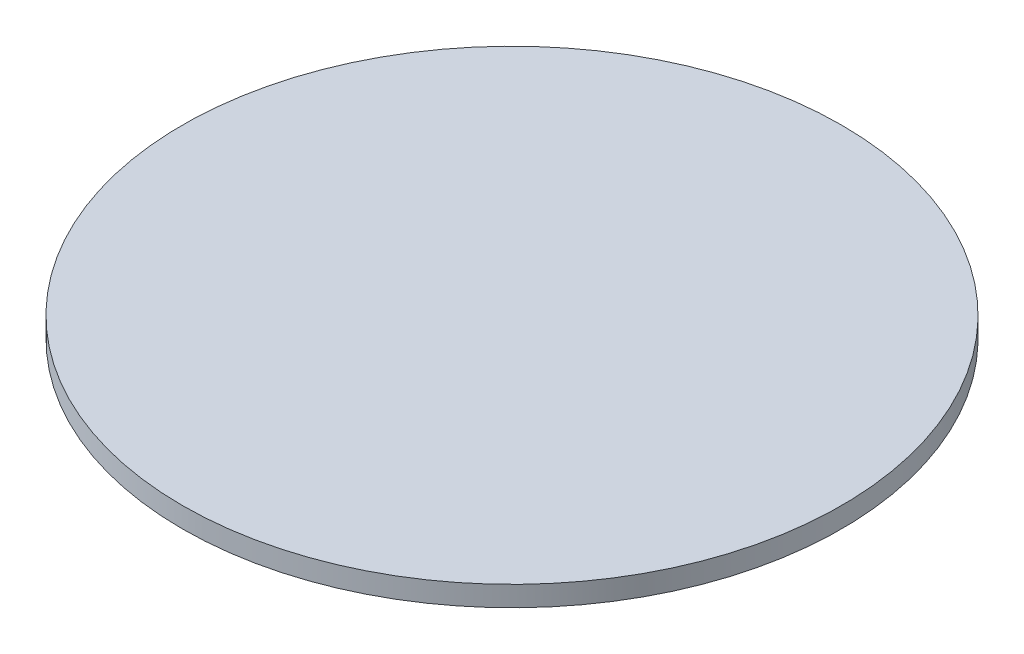
SolidWorks part; units mm, degrees
material "Plain Carbon Steel"
ref_plane "Front Plane" through (0, 0, 0) normal (0, 0, 1) x (1, 0, 0)
ref_plane "Top Plane" through (0, 0, 0) normal (0, 1, 0) x (1, 0, 0)
ref_plane "Right Plane" through (0, 0, 0) normal (1, 0, 0) x (0, 0, -1)
sketch "Sketch1" plane through (0, 0, 0) normal (0, 1, 0) x (1, 0, 0)
  circle A0 centre (0, 0) radius 16.25
  dimension "D1" = 32.5
extrude "Boss-Extrude1" add sketch "Sketch1" along normal blind 1
